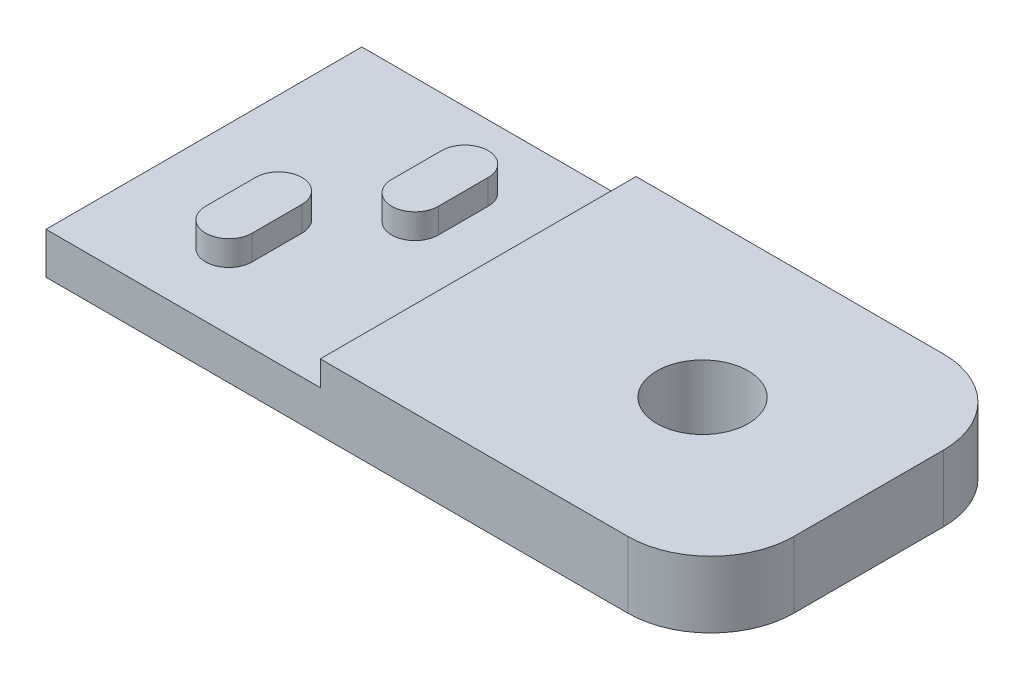
SolidWorks part; units mm, degrees
ref_plane "Front Plane" through (0, 0, 0) normal (0, 0, 1) x (1, 0, 0)
ref_plane "Top Plane" through (0, 0, 0) normal (0, 1, 0) x (1, 0, 0)
ref_plane "Right Plane" through (0, 0, 0) normal (1, 0, 0) x (0, 0, -1)
sketch "Sketch1" plane through (0, 0, 0) normal (0, 1, 0) x (1, 0, 0)
  line L1 (-20, 9.5) -> (20, 9.5)
  line L2 (-20, 9.5) -> (-20, -9.5)
  line L3 (-20, -9.5) -> (20, -9.5)
  line L4 (20, 9.5) -> (20, -9.5)
  line L5 (-20, 9.5) -> (20, -9.5) construction
  line L6 (-20, -9.5) -> (20, 9.5) construction
  point P0 (0, 0)
  dimension "D1" = 19
  dimension "D2" = 40
extrude "Boss-Extrude1" add sketch "Sketch1" along normal blind 4
sketch "Sketch2" plane through (0, 4, 0) normal (0, 1, 0) x (1, 0, 0)
  line L0 (-2.2, 0) -> (2.2, 0) construction
  line L1 (20, -9.5) -> (20, 9.5) construction
  circle A0 centre (10, 0) radius 2.75
  dimension "D1" = 5.5
  dimension "D2" = 10
extrude "Cut-Extrude1" cut sketch "Sketch2" against normal up to next
sketch "Sketch4" plane through (0, 4, 0) normal (0, 1, 0) x (1, 0, 0)
  line L1 (-20, 9.5) -> (-3.5, 9.5)
  line L2 (-20, 9.5) -> (-20, -9.5)
  line L3 (-20, -9.5) -> (-3.5, -9.5)
  line L4 (-3.5, 9.5) -> (-3.5, -9.5)
  line L5 (-9.3, 5) -> (-9.3, 2) construction
  line L6 (-7.9, 5) -> (-7.9, 2)
  line L7 (-10.7, 5) -> (-10.7, 2)
  line L8 (-13.5, -2) -> (-13.5, -5) construction
  line L9 (-12.1, -2) -> (-12.1, -5)
  line L10 (-14.9, -2) -> (-14.9, -5)
  arc A0 (-7.9, 5) -> (-10.7, 5) centre (-9.3, 5) ccw
  arc A1 (-10.7, 2) -> (-7.9, 2) centre (-9.3, 2) ccw
  arc A2 (-12.1, -2) -> (-14.9, -2) centre (-13.5, -2) ccw
  arc A3 (-14.9, -5) -> (-12.1, -5) centre (-13.5, -5) ccw
  point P9 (-9.3, 3.5)
  point P14 (-13.5, -3.5)
  dimension "D4" = 1.4
  dimension "D6" = 1.4
  dimension "D1" = 19
  dimension "D2" = 4.5
  dimension "D3" = 3
  dimension "D5" = 10.7
  dimension "D7" = 3
  dimension "D8" = 4.5
  dimension "D9" = 6.5
  dimension "D10" = 16.5
extrude "Cut-Extrude2" cut sketch "Sketch4" against normal blind 1.5
fillet "Fillet1" radius 5 2 edges at (20, 2, 9.5) (20, 2, -9.5)
